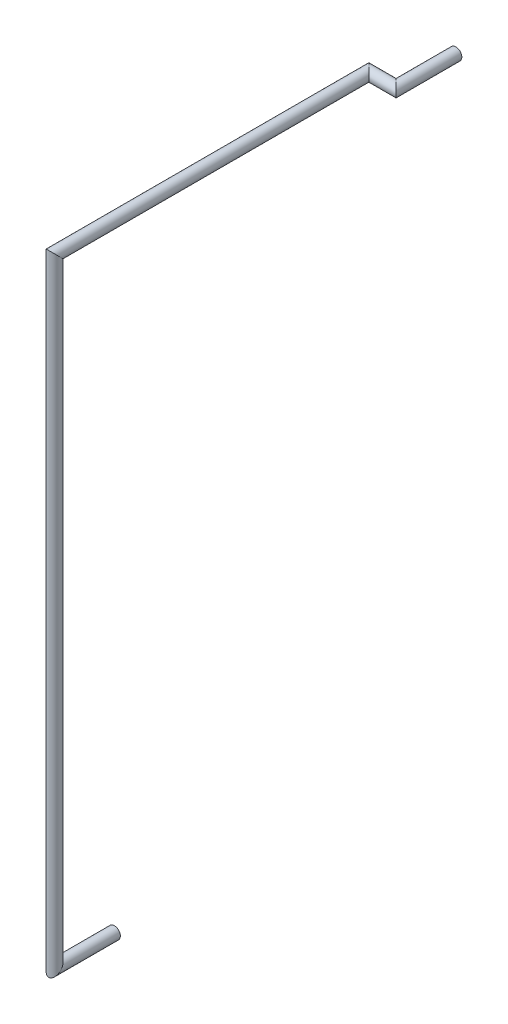
SolidWorks part; units mm, degrees
ref_plane "Plan de face" through (0, 0, 0) normal (1, 0, 0) x (0, 1, 0)
ref_plane "Plan de dessus" through (0, 0, 0) normal (0, 0, 1) x (0, 1, 0)
ref_plane "Plan de droite" through (0, 0, 0) normal (0, 1, 0) x (-1, 0, 0)
sketch3d "Esquisse3D1"
  line L0 (0, 0, 0) -> (0, 0, 5)
  line L1 (0, 0, 5) -> (0, 51.68, 5)
  line L2 (0, 51.68, 5) -> (0, 51.68, -21.29)
  line L3 (0, 51.68, -21.29) -> (2.28, 51.68, -21.29)
  line L4 (2.28, 51.68, -21.29) -> (2.28, 51.68, -26.29)
  dimension "D1" = 5
  dimension "D2" = 51.68
  dimension "D3" = 26.29
  dimension "D4" = 2.28
  dimension "D5" = 5
sketch "Esquisse1" plane through (0, 0, 0) normal (0, 0, 1) x (0, 1, 0)
  circle A0 centre (0, 0) radius 0.5
  dimension "D1" = 1
sweep "Balayage1" add profiles "Esquisse1" path "Esquisse3D1"
